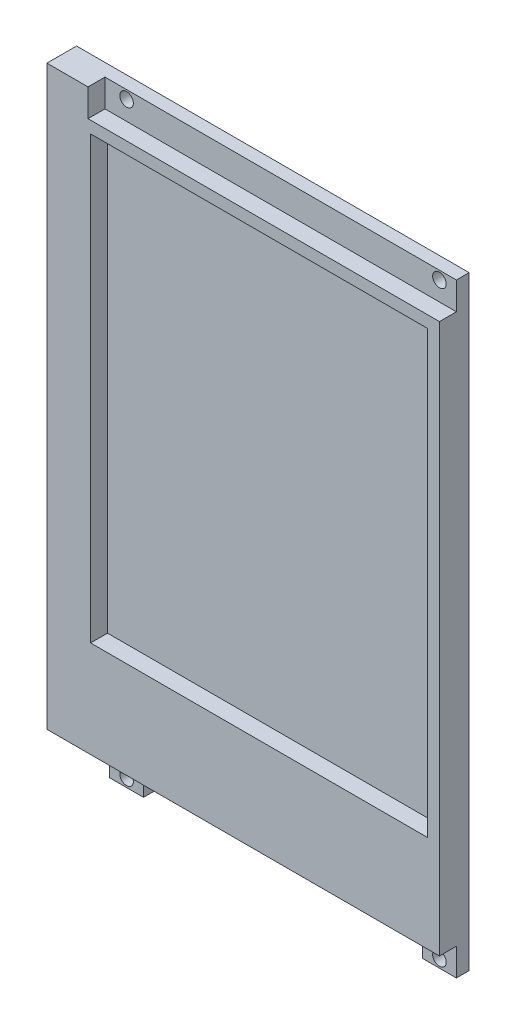
SolidWorks part; units mm, degrees
ref_plane "Plan1" through (0, 0, 0) normal (0, 0, 1) x (1, 0, 0)
ref_plane "Plan2" through (0, 0, 0) normal (0, 1, 0) x (1, 0, 0)
ref_plane "Plan3" through (0, 0, 0) normal (1, 0, 0) x (0, 0, -1)
sketch "Esquisse1" plane through (0, 0, 0) normal (0, 0, 1) x (1, 0, 0)
  line L0 (-45, 46) -> (-45, -96.6)
  line L1 (-45, -96.6) -> (47.6, -96.6)
  line L2 (47.6, -96.6) -> (47.6, 46)
  line L3 (47.6, 46) -> (-45, 46)
  dimension "D1" = 92.6
  dimension "D2" = 142.6
extrude "Base-Extrusion" add sketch "Esquisse1" along normal blind 7
sketch "Esquisse2" plane through (0, 0, 7) normal (0, 0, 1) x (1, 0, 0)
  line L0 (-34.7, 36.7) -> (44.8, 36.7)
  line L1 (-34.7, 36.7) -> (-34.7, -67.3)
  line L2 (44.8, 36.7) -> (44.8, -67.3)
  line L3 (-34.7, -67.3) -> (44.8, -67.3)
  line L4 (-45, 46) -> (-45, -96.6) construction
  line L5 (47.6, 46) -> (-45, 46) construction
  dimension "D1" = 10.3
  dimension "D2" = 9.3
  dimension "D3" = 104
  dimension "D4" = 79.5
  dimension "D5" = 79.5
sketch "Esquisse4" plane through (0, 0, 7) normal (0, 0, 1) x (1, 0, 0)
  line L0 (-45, 46) -> (-45, -96.6) construction
  circle A0 centre (-30.2, 44) radius 1.6
  circle A1 centre (43.6, 44) radius 1.6
  circle A2 centre (-30.2, -94.6) radius 1.6
  circle A3 centre (43.6, -94.6) radius 1.6
  dimension "D1" = 14.8
  dimension "D2" = 73.8
extrude "Enlèv. mat.-Extru.2" cut sketch "Esquisse4" against normal through all
extrude "Enlèv. mat.-Extru.3" cut sketch "Esquisse2" against normal blind 4
sketch "Esquisse6" plane through (0, 0, 7) normal (0, 0, 1) x (1, 0, 0)
  line L0 (-35.3, 49) -> (-35.3, 39.5)
  line L1 (-45, 46) -> (-45, -96.6) construction
  line L2 (-35.3, 39.5) -> (51, 39.5)
  line L3 (47.6, 46) -> (-45, 46) construction
  line L4 (-35.3, 49) -> (51, 49)
  line L5 (51, 49) -> (51, 39.5)
  dimension "D1" = 9.7
  dimension "D2" = 6.5
extrude "Enlèv. mat.-Extru.4" cut sketch "Esquisse6" against normal blind 4
sketch "Esquisse7" plane through (0, 0, 7) normal (0, 0, 1) x (1, 0, 0)
  line L0 (-60, -90.1) -> (60, -90.1)
  line L1 (-35.3, 39.5) -> (47.6, 39.5) construction
  line L2 (60, -108) -> (-60, -108)
  line L3 (-60, -108) -> (-60, -90.1)
  line L4 (60, -90.1) -> (60, -108)
  dimension "D1" = 129.6
extrude "Enlèv. mat.-Extru.6" cut sketch "Esquisse7" against normal blind 4
sketch "Esquisse8" plane through (0, 0, 0) normal (0, 0, -1) x (-1, 0, 0)
  line L0 (34.2, -90.1) -> (34.2, -99)
  line L1 (48, -99) -> (34.2, -99)
  line L2 (-39.6, -90.1) -> (-39.6, -99)
  line L3 (26.2, -90.1) -> (26.2, -99)
  line L4 (-39.6, -90.1) -> (26.2, -90.1)
  line L5 (45, -96.6) -> (-47.6, -96.6) construction
  line L6 (34.2, -90.1) -> (48, -90.1)
  line L7 (26.2, -99) -> (-39.6, -99)
  line L8 (48, -90.1) -> (48, -99)
  dimension "D3" = 6.5
extrude "Enlèv. mat.-Extru.7" cut sketch "Esquisse8" against normal blind 15
sketch "Esquisse9" plane through (0, 0, 0) normal (0, 0, -1) x (-1, 0, 0)
  line L0 (-5.1, -61) -> (-5.1, -104) construction
  line L1 (45, 46) -> (45, -90.1) construction
  dimension "D1" = 50.1
